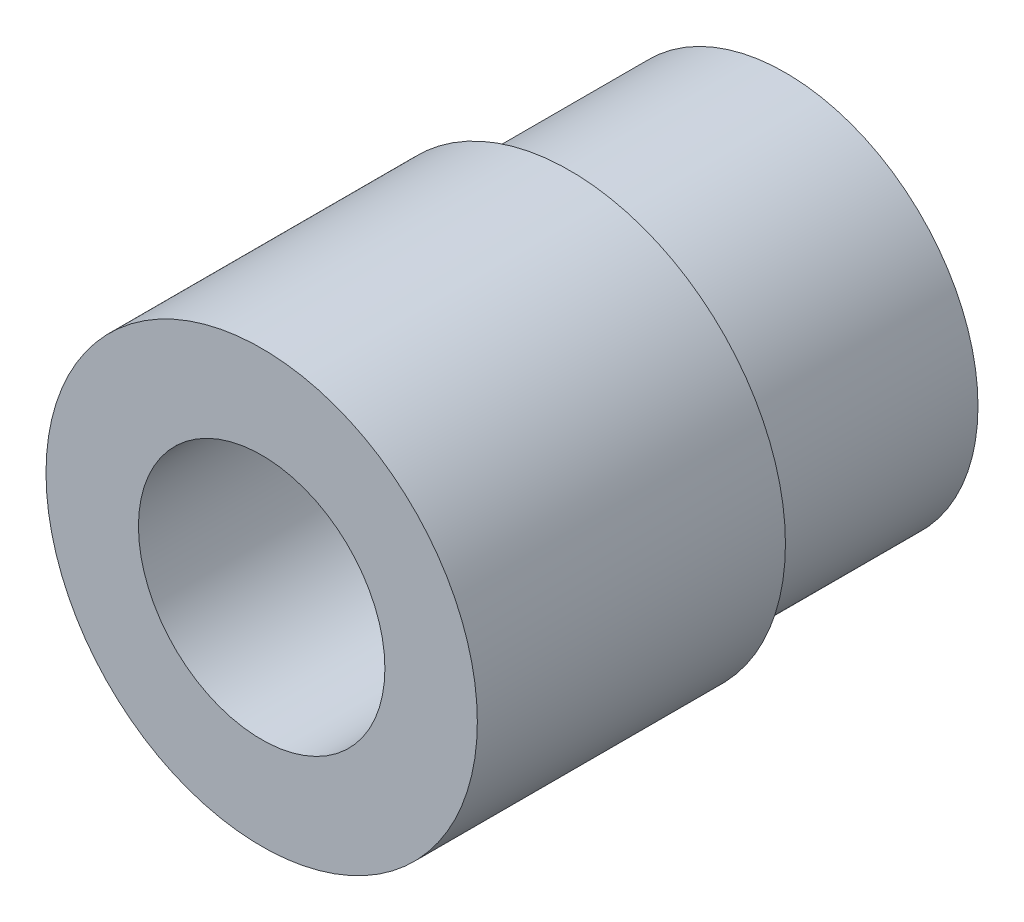
SolidWorks part; units mm, degrees
material "Plain Carbon Steel"
ref_plane "Front Plane" through (0, 0, 0) normal (0, 0, 1) x (1, 0, 0)
ref_plane "Top Plane" through (0, 0, 0) normal (0, 1, 0) x (1, 0, 0)
ref_plane "Right Plane" through (0, 0, 0) normal (1, 0, 0) x (0, 0, -1)
sketch "Sketch1" plane through (0, 0, 0) normal (0, 0, 1) x (1, 0, 0)
  circle A0 centre (0, 0) radius 12.5
  dimension "D1" = 25
extrude "SmallO.D." add sketch "Sketch1" along normal blind 14
sketch "Sketch2" plane through (0, 0, 14) normal (0, 0, 1) x (1, 0, 0)
  circle A0 centre (0, 0) radius 14
  dimension "D1" = 28
extrude "LargeO.D." add sketch "Sketch2" along normal blind 20
sketch "Sketch3" plane through (0, 0, 34) normal (0, 0, 1) x (1, 0, 0)
  circle A0 centre (0, 0) radius 8
  dimension "D1" = 16
extrude "Bore" cut sketch "Sketch3" against normal through all
